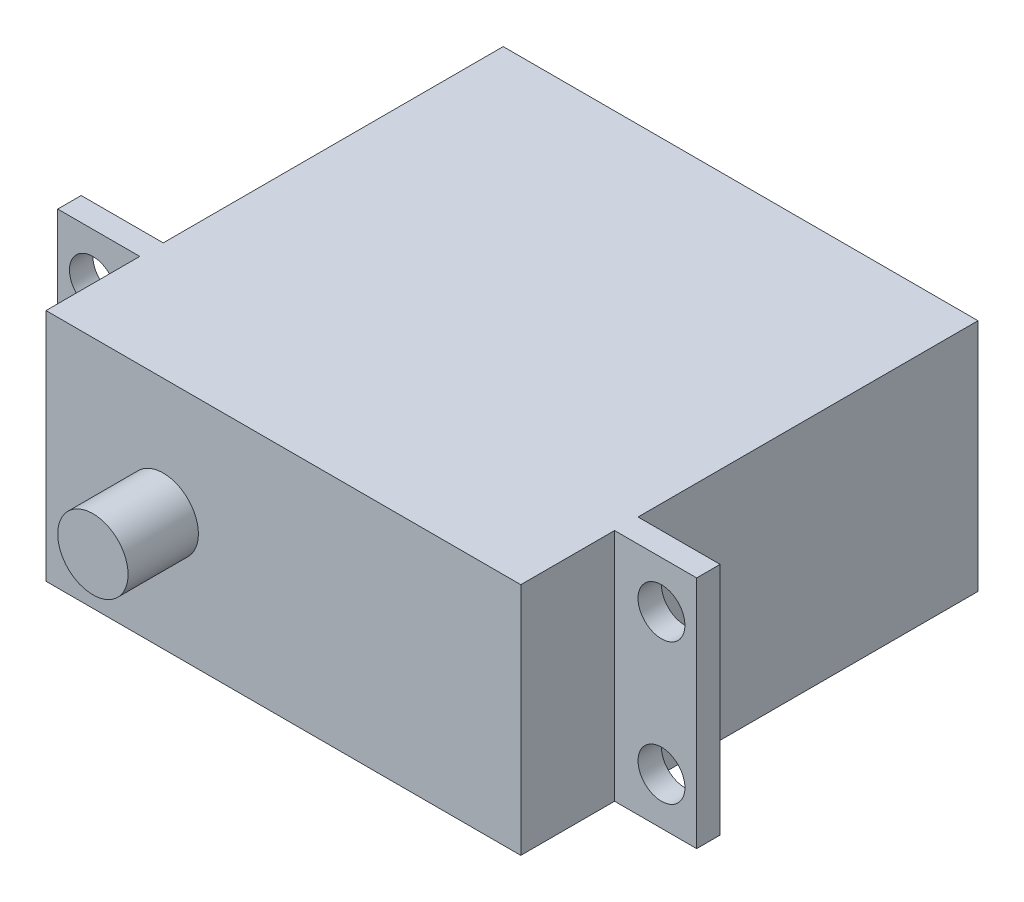
SolidWorks part; units mm, degrees
ref_plane "Front Plane" through (0, 0, 0) normal (0, 0, 1) x (1, 0, 0)
ref_plane "Top Plane" through (0, 0, 0) normal (0, 1, 0) x (1, 0, 0)
ref_plane "Right Plane" through (0, 0, 0) normal (1, 0, 0) x (0, 0, -1)
sketch "Sketch1" plane through (0, 0, 0) normal (0, 0, 1) x (1, 0, 0)
  line L1 (-20.25, 10) -> (20.25, 10)
  line L2 (-20.25, 10) -> (-20.25, -10)
  line L3 (-20.25, -10) -> (20.25, -10)
  line L4 (20.25, 10) -> (20.25, -10)
  line L5 (-20.25, 10) -> (20.25, -10) construction
  line L6 (-20.25, -10) -> (20.25, 10) construction
  point P0 (0, 0)
  dimension "D1" = 20
  dimension "D2" = 40.5
extrude "Boss-Extrude1" add sketch "Sketch1" along normal blind 39
sketch "Sketch2" plane through (0, 0, 39) normal (0, 0, 1) x (1, 0, 0)
  line L0 (-20.25, 10) -> (-20.25, -10) construction
  circle A0 centre (-10.25, 0) radius 3
  dimension "D1" = 6
  dimension "D2" = 10
extrude "Boss-Extrude2" add sketch "Sketch2" along normal blind 6
sketch "Sketch3" plane through (-20.25, 0, 0) normal (-1, 0, 0) x (0, 0, 1)
  line L0 (39, 10) -> (0, 10) construction
  line L1 (29, 10) -> (31, 10)
  line L2 (29, 10) -> (29, -10)
  line L3 (29, -10) -> (31, -10)
  line L4 (31, 10) -> (31, -10)
  line L5 (39, -10) -> (0, -10) construction
  line L6 (39, 10) -> (39, -10) construction
  dimension "D1" = 2
  dimension "D2" = 8
extrude "Boss-Extrude3" add sketch "Sketch3" along normal blind 7
sketch "Sketch4" plane through (0, 0, 31) normal (0, 0, 1) x (1, 0, 0)
  line L0 (-20.25, 10) -> (-20.25, -10) construction
  line L1 (-27.25, 10) -> (-20.25, 10) construction
  line L2 (24.75, 0) -> (-24.75, 0) construction
  circle A0 centre (-24.25, 6) radius 2
  circle A1 centre (-24.25, -6) radius 2
  dimension "D1" = 4
  dimension "D2" = 4
  dimension "D3" = 4
extrude "Cut-Extrude1" cut sketch "Sketch4" against normal blind 7
mirror "Mirror1" about plane through (0, 0, 0) normal (1, 0, 0) of "Cut-Extrude1", "Boss-Extrude3"
sketch "Sketch5" plane through (0, 0, 0) normal (0, 0, -1) x (-1, 0, 0)
  circle A0 centre (-24.25, 6) radius 2
  circle A1 centre (-24.25, -6) radius 2
  circle A2 centre (24.25, 6) radius 2
  circle A3 centre (24.25, -6) radius 2
